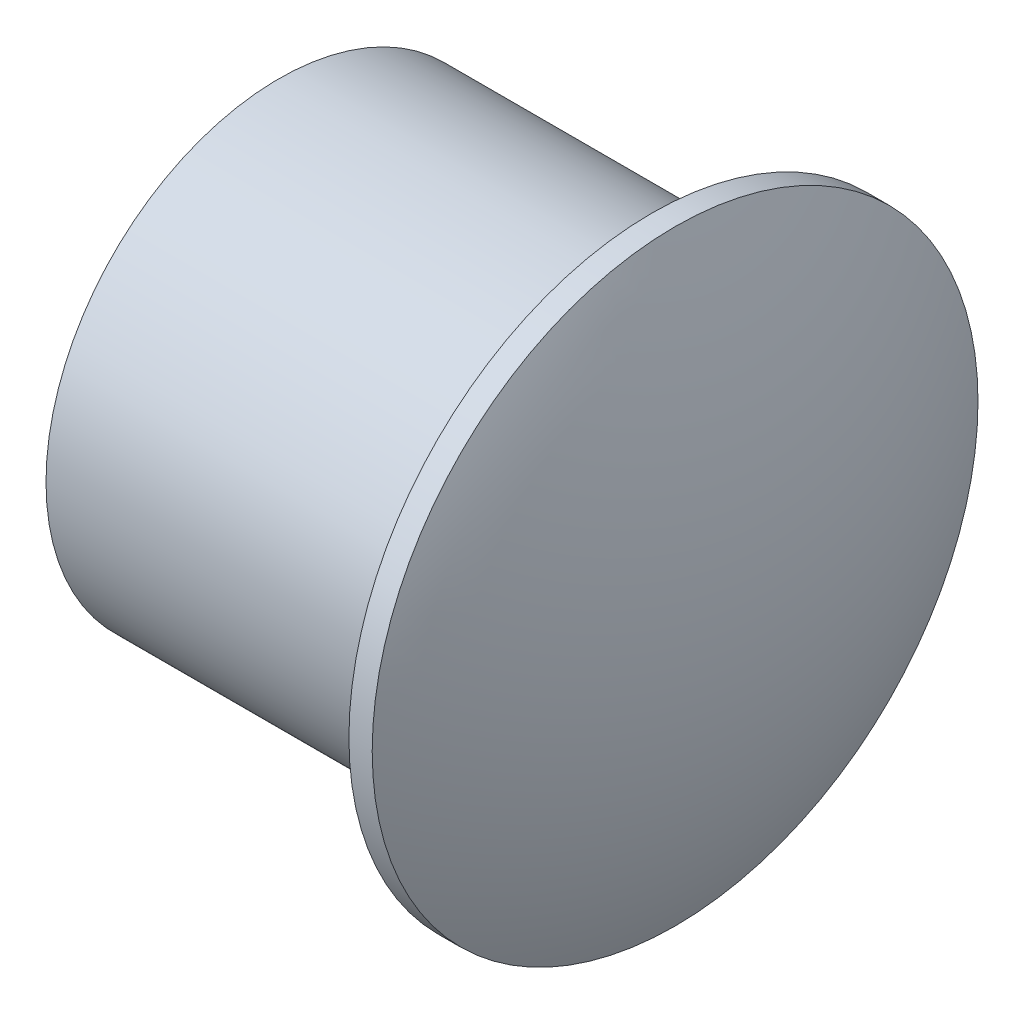
SolidWorks part; units mm, degrees
ref_plane "Front Plane" through (0, 0, 0) normal (0, 0, 1) x (1, 0, 0)
ref_plane "Top Plane" through (0, 0, 0) normal (0, 1, 0) x (1, 0, 0)
ref_plane "Right Plane" through (0, 0, 0) normal (1, 0, 0) x (0, 0, -1)
sketch "Sketch1" plane through (0, 0, 0) normal (0, 0, 1) x (1, 0, 0)
  line L0 (0, 0) -> (0, 10)
  line L1 (0, 10) -> (16, 10)
  line L2 (16, 10) -> (16, 13)
  line L3 (16, 13) -> (17, 13)
  line L4 (0, 0) -> (20, 0)
  arc A0 (17, 13) -> (20, 0) centre (-9.6667, 0) cw
  point P8 (16, 8.7284)
  point P9 (18.264, 11.3003)
  point P10 (16.5, 13)
  point P11 (0, 0)
  dimension "D1" = 20
  dimension "D2" = 16
  dimension "D3" = 10
  dimension "D4" = 1
  dimension "D5" = 3
revolve "Revolve1" add sketch "Sketch1" angle 360 about L4
